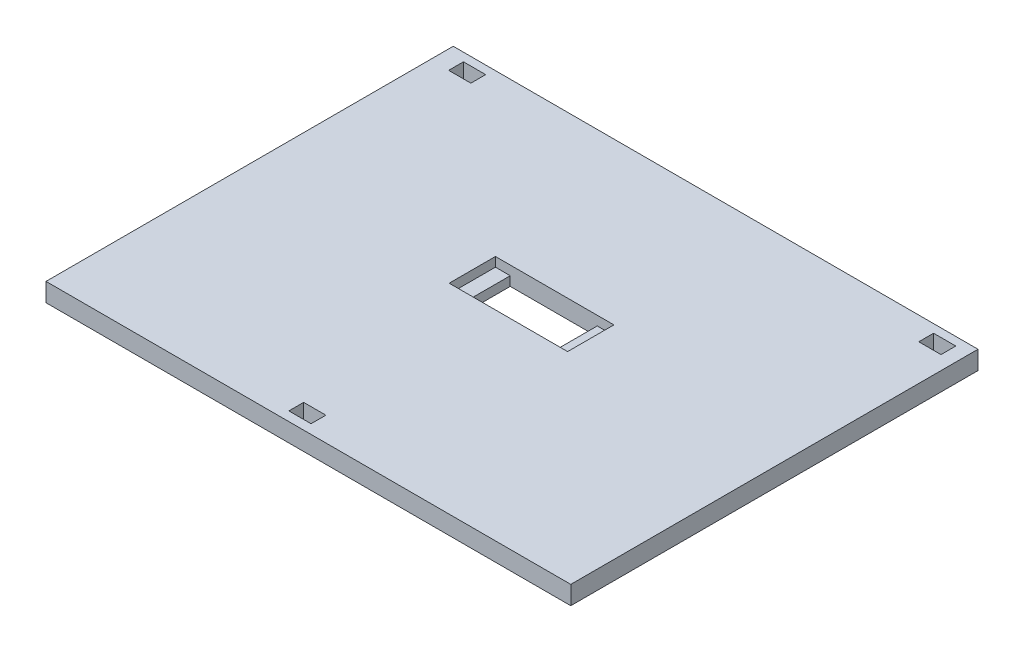
SolidWorks part; units mm, degrees
ref_plane "Front Plane" through (0, 0, 0) normal (0, 0, 1) x (1, 0, 0)
ref_plane "Top Plane" through (0, 0, 0) normal (0, 1, 0) x (1, 0, 0)
ref_plane "Right Plane" through (0, 0, 0) normal (1, 0, 0) x (0, 0, -1)
sketch "Sketch3" plane through (0, 0, 0) normal (0, 1, 0) x (1, 0, 0)
  line L1 (-82.684, 35.7689) -> (61.334, 35.7689)
  line L2 (-82.684, 35.7689) -> (-82.684, -75.9911)
  line L3 (-82.684, -75.9911) -> (61.334, -75.9911)
  line L4 (61.334, 35.7689) -> (61.334, -75.9911)
  dimension "D1" = 144.018
  dimension "D2" = 111.76
extrude "Boss-Extrude2" add sketch "Sketch3" along normal blind 5.08
sketch "Sketch5" plane through (0, 5.08, 0) normal (0, 1, 0) x (1, 0, 0)
  line L0 (-82.684, 35.7689) -> (-82.684, -75.9911) construction
  line L1 (-77.5921, 33.4829) -> (-71.4961, 33.4829)
  line L2 (-77.5921, 33.4829) -> (-77.5921, 29.4189)
  line L3 (-77.5921, 29.4189) -> (-71.4961, 29.4189)
  line L4 (-71.4961, 33.4829) -> (-71.4961, 29.4189)
  line L5 (61.334, 35.7689) -> (-82.684, 35.7689) construction
  line L6 (61.334, -75.9911) -> (61.334, 35.7689) construction
  line L7 (51.428, 33.4829) -> (57.524, 33.4829)
  line L8 (51.428, 33.4829) -> (51.428, 29.4189)
  line L9 (51.428, 29.4189) -> (57.524, 29.4189)
  line L10 (57.524, 33.4829) -> (57.524, 29.4189)
  line L11 (-82.684, -75.9911) -> (61.334, -75.9911) construction
  line L12 (-18.5794, -69.3871) -> (-12.4834, -69.3871)
  line L13 (-18.5794, -69.3871) -> (-18.5794, -73.4511)
  line L14 (-18.5794, -73.4511) -> (-12.4834, -73.4511)
  line L15 (-12.4834, -69.3871) -> (-12.4834, -73.4511)
  dimension "D1" = 6.096
  dimension "D2" = 4.064
  dimension "D3" = 11.1878
  dimension "D4" = 2.286
  dimension "D5" = 6.096
  dimension "D6" = 4.064
  dimension "D7" = 9.906
  dimension "D8" = 6.096
  dimension "D9" = 4.064
  dimension "D10" = 2.54
extrude "Cut-Extrude1" cut sketch "Sketch5" against normal blind 5.08
sketch "Sketch6" plane through (0, 5.08, 0) normal (0, 1, 0) x (1, 0, 0)
  line L0 (-82.684, 35.7689) -> (-82.684, -75.9911) construction
  line L1 (-26.931, -8.4006) -> (5.581, -8.4006)
  line L2 (-26.931, -8.4006) -> (-26.931, -21.1006)
  line L3 (-26.931, -21.1006) -> (5.581, -21.1006)
  line L4 (5.581, -8.4006) -> (5.581, -21.1006)
  dimension "D1" = 32.512
  dimension "D2" = 12.7
  dimension "D3" = 55.753
extrude "Cut-Extrude2" cut sketch "Sketch6" against normal blind 2.54
sketch "Sketch7" plane through (0, 2.54, 0) normal (0, 1, 0) x (1, 0, 0)
  line L0 (5.581, -8.4006) -> (-26.931, -8.4006) construction
  line L1 (-22.867, -8.4006) -> (1.009, -8.4006)
  line L2 (-22.867, -8.4006) -> (-22.867, -21.1006)
  line L3 (-22.867, -21.1006) -> (1.009, -21.1006)
  line L4 (1.009, -8.4006) -> (1.009, -21.1006)
  line L5 (-26.931, -21.1006) -> (5.581, -21.1006) construction
  line L6 (5.581, -21.1006) -> (5.581, -8.4006) construction
  dimension "D1" = 23.876
  dimension "D2" = 4.572
extrude "Cut-Extrude3" cut sketch "Sketch7" against normal blind 2.54
